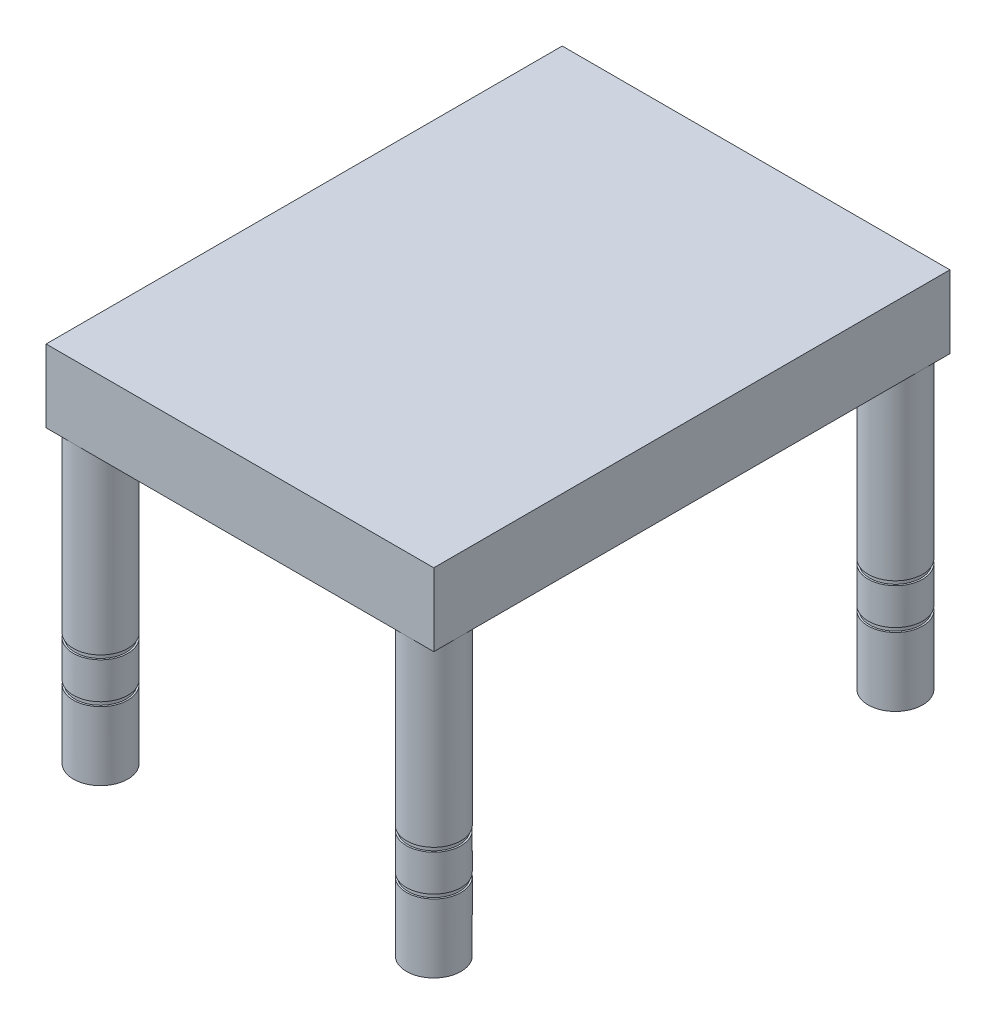
SolidWorks part; units mm, degrees
ref_plane "Front Plane" through (0, 0, 0) normal (0, 0, 1) x (1, 0, 0)
ref_plane "Top Plane" through (0, 0, 0) normal (0, 1, 0) x (1, 0, 0)
ref_plane "Right Plane" through (0, 0, 0) normal (1, 0, 0) x (0, 0, -1)
sketch "Sketch1" plane through (0, 0, 0) normal (0, 1, 0) x (1, 0, 0)
  circle A0 centre (-29.12, 40.3467) radius 4.7625
  circle A1 centre (-29.12, -40.3467) radius 4.7625
  circle A2 centre (29.12, -40.3467) radius 4.7625
  circle A3 centre (29.12, 40.3467) radius 4.7625
  dimension "D1" = 80.6935
  dimension "D3" = 9.525
  dimension "D4" = 9.525
  dimension "D5" = 9.525
  dimension "D6" = 9.525
  dimension "D7" = 40.3467
  dimension "D2" = 58.24
  dimension "D8" = 29.12
extrude "Boss-Extrude1" add sketch "Sketch1" along normal blind 50.8
sketch "Sketch2" plane through (0, 50.8, 0) normal (0, 1, 0) x (1, 0, 0)
  line L1 (-33.8825, 45.1092) -> (33.8825, 45.1092)
  line L2 (-33.8825, 45.1092) -> (-33.8825, -45.1092)
  line L3 (-33.8825, -45.1092) -> (33.8825, -45.1092)
  line L4 (33.8825, 45.1092) -> (33.8825, -45.1092)
  circle A0 centre (-29.12, 40.3467) radius 4.7625 construction
  circle A1 centre (29.12, 40.3467) radius 4.7625 construction
  circle A2 centre (-29.12, -40.3467) radius 4.7625 construction
extrude "Boss-Extrude2" add sketch "Sketch2" along normal blind 12.7
sketch3d "3DSketch1"
  circle A0 centre (-29.12, 12.7, 40.3467) radius 4.7625
  circle A1 centre (29.12, 12.7, 40.3467) radius 4.7625
  circle A2 centre (29.12, 12.7, -40.3467) radius 4.7625
  circle A3 centre (-29.12, 12.7, -40.3467) radius 4.7625
  circle A4 centre (-29.12, 0, -40.3467) radius 4.7625 construction
  circle A5 centre (-29.12, 0, 40.3467) radius 4.7625 construction
  circle A6 centre (29.12, 0, 40.3467) radius 4.7625 construction
  circle A7 centre (29.12, 0, -40.3467) radius 4.7625 construction
  point P2 (-29.12, 7.9375, 40.3467)
  point P5 (29.12, 7.9375, 40.3467)
  point P8 (29.12, 7.9375, -40.3467)
  point P11 (-29.12, 7.9375, -40.3467)
  point P15 (-29.12, 4.7625, -40.3467)
  point P18 (-29.12, 4.7625, 40.3467)
  point P22 (29.12, 4.7625, 40.3467)
  point P26 (29.12, 4.7625, -40.3467)
  dimension "D2" = 9.525
  dimension "D3" = 9.525
  dimension "D4" = 9.525
  dimension "D5" = 9.525
  dimension "D1" = 12.7
extrude "Cut-Extrude1" cut sketch "3DSketch1" along direction (0, 1, 0) on the side against the normal blind 0.7366
sketch "Sketch3" plane through (0, 12.7, 0) normal (0, -1, 0) x (-1, 0, 0)
  circle A0 centre (29.12, 40.3467) radius 4.4704
  circle A1 centre (-29.12, 40.3467) radius 4.4704
  circle A2 centre (-29.12, -40.3467) radius 4.4704
  circle A3 centre (29.12, -40.3467) radius 4.4704
  dimension "D1" = 8.9408
  dimension "D2" = 8.9408
  dimension "D3" = 8.9408
  dimension "D4" = 8.9408
extrude "Boss-Extrude3" add sketch "Sketch3" along normal up to surface (0.7366 mm away) up to face at (-29.12, 11.9634, 35.5842)
sketch3d "3DSketch2"
  circle A0 centre (-29.12, 19.05, 40.3467) radius 5.08
  circle A1 centre (29.12, 19.05, 40.3467) radius 5.08
  circle A2 centre (29.12, 19.05, -40.3467) radius 5.08
  circle A3 centre (-29.12, 19.05, -40.3467) radius 5.08
  circle A4 centre (-29.12, 0, -40.3467) radius 4.7625 construction
  circle A5 centre (-29.12, 0, 40.3467) radius 4.7625 construction
  circle A6 centre (29.12, 0, 40.3467) radius 4.7625 construction
  circle A7 centre (29.12, 0, -40.3467) radius 4.7625 construction
  point P2 (-29.12, 13.97, 40.3467)
  point P5 (29.12, 13.97, 40.3467)
  point P8 (29.12, 13.97, -40.3467)
  point P11 (-29.12, 13.97, -40.3467)
  point P15 (-29.12, 4.7625, -40.3467)
  point P18 (-29.12, 4.7625, 40.3467)
  point P22 (29.12, 4.7625, 40.3467)
  point P26 (29.12, 4.7625, -40.3467)
  dimension "D2" = 10.16
  dimension "D3" = 10.16
  dimension "D4" = 10.16
  dimension "D5" = 10.16
  dimension "D1" = 19.05
extrude "Cut-Extrude2" cut sketch "3DSketch2" along direction (0, 1, 0) on the side of the normal blind 0.7366
sketch "Sketch4" plane through (0, 19.7866, 0) normal (0, -1, 0) x (-1, 0, 0)
  circle A0 centre (29.12, -40.3467) radius 4.4704
  circle A1 centre (-29.12, -40.3467) radius 4.4704
  circle A2 centre (-29.12, 40.3467) radius 4.4704
  circle A3 centre (29.12, 40.3467) radius 4.4704
  dimension "D1" = 8.9408
  dimension "D2" = 8.9408
  dimension "D3" = 8.9408
  dimension "D4" = 8.9408
extrude "Boss-Extrude4" add sketch "Sketch4" along normal up to surface (0.7366 mm away) up to face at (-29.12, 19.05, -35.5842)
